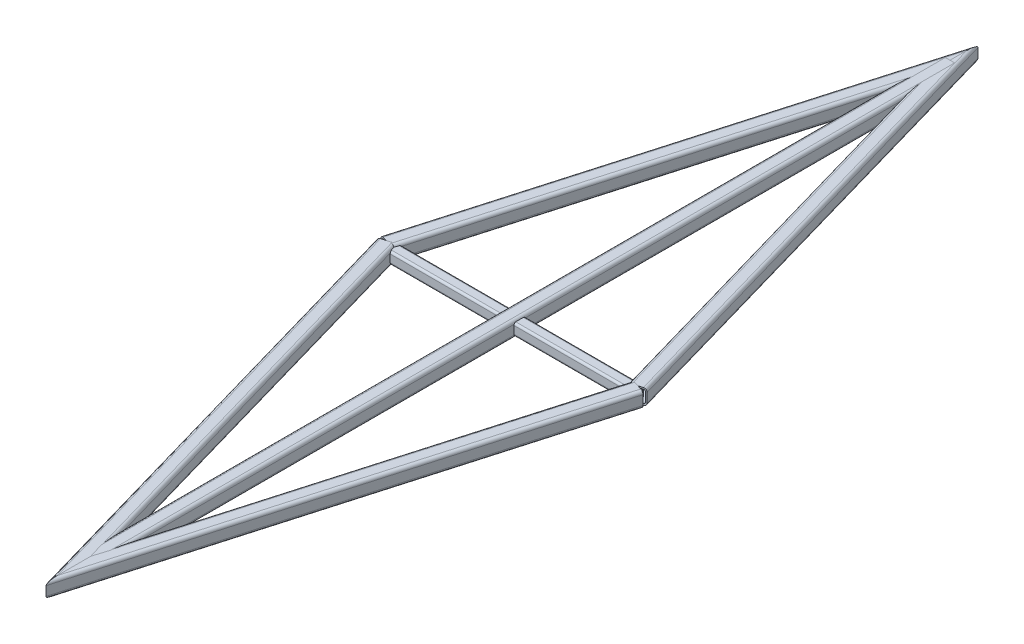
SolidWorks part; units mm, degrees
ref_plane "Front Plane" through (0, 0, 0) normal (0, 0, 1) x (1, 0, 0)
ref_plane "Top Plane" through (0, 0, 0) normal (0, 1, 0) x (1, 0, 0)
ref_plane "Right Plane" through (0, 0, 0) normal (1, 0, 0) x (0, 0, -1)
sketch "Sketch1" plane through (0, 0, 0) normal (0, 1, 0) x (1, 0, 0)
  circle A0 centre (0, 0) radius 465
  dimension "D1" = 930
sketch3d "3DSketch2"
  line L0 (325, 0, 332.5658) -> (325, 0, 1132.5658) construction
  line L1 (325, 0, 1132.5658) -> (-325, 0, 1132.5658) construction
  line L2 (-325, 0, 1132.5658) -> (-325, 0, 332.5658) construction
  line L3 (0, 0, 1132.5658) -> (0, 0, -1132.5658) construction
  line L4 (-465, 0, 0) -> (465, 0, 0) construction
  line L5 (325, 0, -332.5658) -> (325, 0, -1132.5658) construction
  line L6 (325, 0, -1132.5658) -> (-325, 0, -1132.5658) construction
  line L7 (-325, 0, -1132.5658) -> (-325, 0, -332.5658) construction
  line L8 (0, 0, 1132.5658) -> (0, 500, 1132.5658) construction
  line L11 (325, 0, 332.5658) -> (325, 500, 332.5658) construction
  line L12 (-325, 0, 332.5658) -> (-325, 500, 332.5658) construction
  line L13 (325, 500, 332.5658) -> (325, 500, -332.5658) construction
  line L16 (325, 0, -332.5658) -> (325, 500, -332.5658) construction
  line L17 (0, 500, 1132.5658) -> (325, 500, 0)
  line L19 (0, 500, 1132.5658) -> (-325, 500, 0)
  line L23 (0, 500, -1132.5658) -> (325, 500, 0)
  line L26 (0, 500, -1132.5658) -> (-325, 500, 0)
  line L28 (0, 500, 1132.5658) -> (0, 500, -1132.5658)
  line L29 (-325, 500, 0) -> (325, 500, 0) construction
  line L30 (325, 500, 0) -> (0, 500, 0) construction
  line L31 (0, 500, 0) -> (-325, 500, 0) construction
  line L42 (0, 500, 0) -> (325, 500, 0)
  line L43 (0, 500, 0) -> (-325, 500, 0)
  circle A0 centre (0, 0, 0) radius 465 construction
  point P4 (0, 465, 0)
  point P7 (0, 0, 1132.5658)
  point P14 (0, 0, 0)
  point P28 (0, 500, 500)
  dimension "D1" = 325
  dimension "D2" = 800
  dimension "D3" = 500
  dimension "D4" = 500
  dimension "D5" = 500
other "Square tube 40 X 40 X 4(2)"
ref_plane "Plane5" through (0, 500, -1132.5658) normal (0.2758, 0, 0.9612) x (0.9612, 0, -0.2758)
sketch "Sketch117" plane through (0, 500, -1132.5658) normal (0.2758, 0, 0.9612) x (0.9612, 0, -0.2758)
  line L0 (-12, -16) -> (12, -16)
  line L1 (-16, -12) -> (-16, 12)
  line L2 (12, 16) -> (-12, 16)
  line L3 (16, 12) -> (16, -12)
  line L4 (-12, -20) -> (12, -20)
  line L5 (-20, -12) -> (-20, 12)
  line L6 (12, 20) -> (-12, 20)
  line L7 (20, 12) -> (20, -12)
  arc A0 (20, 12) -> (12, 20) centre (12, 12) ccw
  arc A1 (12, -20) -> (20, -12) centre (12, -12) ccw
  arc A2 (-20, -12) -> (-12, -20) centre (-12, -12) ccw
  arc A3 (-12, 20) -> (-20, 12) centre (-12, 12) ccw
  arc A4 (-12, 16) -> (-16, 12) centre (-12, 12) ccw
  arc A5 (16, 12) -> (12, 16) centre (12, 12) ccw
  arc A6 (12, -16) -> (16, -12) centre (12, -12) ccw
  arc A7 (-16, -12) -> (-12, -16) centre (-12, -12) ccw
  point P0 (-20, 0)
  point P1 (20, 0)
  point P2 (0, 20)
  point P3 (0, -20)
  point P4 (0, 0)
  point P5 (-20, -20)
  point P6 (20, -20)
  point P7 (20, 20)
  point P8 (-20, 20)
  point P33 (0, 0)
  dimension "D1" = 8
  dimension "Thickness" = 4
  dimension "V_leg" = 40
other "Square tube 40 X 40 X 4(3)"
ref_plane "Plane6" through (0, 500, 1132.5658) normal (0, 0, -1) x (1, 0, 0)
sketch "Sketch118" plane through (0, 500, 1132.5658) normal (0, 0, -1) x (1, 0, 0)
  line L0 (-12, -16) -> (12, -16)
  line L1 (-16, -12) -> (-16, 12)
  line L2 (12, 16) -> (-12, 16)
  line L3 (16, 12) -> (16, -12)
  line L4 (-12, -20) -> (12, -20)
  line L5 (-20, -12) -> (-20, 12)
  line L6 (12, 20) -> (-12, 20)
  line L7 (20, 12) -> (20, -12)
  arc A0 (20, 12) -> (12, 20) centre (12, 12) ccw
  arc A1 (12, -20) -> (20, -12) centre (12, -12) ccw
  arc A2 (-20, -12) -> (-12, -20) centre (-12, -12) ccw
  arc A3 (-12, 20) -> (-20, 12) centre (-12, 12) ccw
  arc A4 (-12, 16) -> (-16, 12) centre (-12, 12) ccw
  arc A5 (16, 12) -> (12, 16) centre (12, 12) ccw
  arc A6 (12, -16) -> (16, -12) centre (12, -12) ccw
  arc A7 (-16, -12) -> (-12, -16) centre (-12, -12) ccw
  point P0 (-20, 0)
  point P1 (20, 0)
  point P2 (0, 20)
  point P3 (0, -20)
  point P4 (0, 0)
  point P5 (-20, -20)
  point P6 (20, -20)
  point P7 (20, 20)
  point P8 (-20, 20)
  point P33 (0, 0)
  dimension "D1" = 8
  dimension "Thickness" = 4
  dimension "V_leg" = 40
other "Square tube 40 X 40 X 4(4)"
ref_plane "Plane7" through (0, 500, 1132.5658) normal (0.2758, 0, -0.9612) x (-0.9612, 0, -0.2758)
sketch "Sketch119" plane through (0, 500, 1132.5658) normal (0.2758, 0, -0.9612) x (-0.9612, 0, -0.2758)
  line L0 (-12, -16) -> (12, -16)
  line L1 (-16, -12) -> (-16, 12)
  line L2 (12, 16) -> (-12, 16)
  line L3 (16, 12) -> (16, -12)
  line L4 (-12, -20) -> (12, -20)
  line L5 (-20, -12) -> (-20, 12)
  line L6 (12, 20) -> (-12, 20)
  line L7 (20, 12) -> (20, -12)
  arc A0 (20, 12) -> (12, 20) centre (12, 12) ccw
  arc A1 (12, -20) -> (20, -12) centre (12, -12) ccw
  arc A2 (-20, -12) -> (-12, -20) centre (-12, -12) ccw
  arc A3 (-12, 20) -> (-20, 12) centre (-12, 12) ccw
  arc A4 (-12, 16) -> (-16, 12) centre (-12, 12) ccw
  arc A5 (16, 12) -> (12, 16) centre (12, 12) ccw
  arc A6 (12, -16) -> (16, -12) centre (12, -12) ccw
  arc A7 (-16, -12) -> (-12, -16) centre (-12, -12) ccw
  point P0 (-20, 0)
  point P1 (20, 0)
  point P2 (0, 20)
  point P3 (0, -20)
  point P4 (0, 0)
  point P5 (-20, -20)
  point P6 (20, -20)
  point P7 (20, 20)
  point P8 (-20, 20)
  point P33 (0, 0)
  dimension "D1" = 8
  dimension "Thickness" = 4
  dimension "V_leg" = 40
other "Square tube 30 X 30 X 2.6(8)"
ref_plane "Plane9" through (0, 500, 0) normal (1, 0, 0) x (0, 0, -1)
sketch "Sketch123" plane through (0, 500, 0) normal (1, 0, 0) x (0, 0, -1)
  line L0 (-9.8, -12.4) -> (9.8, -12.4)
  line L1 (-12.4, -9.8) -> (-12.4, 9.8)
  line L2 (9.8, 12.4) -> (-9.8, 12.4)
  line L3 (12.4, 9.8) -> (12.4, -9.8)
  line L4 (-9.8, -15) -> (9.8, -15)
  line L5 (-15, -9.8) -> (-15, 9.8)
  line L6 (9.8, 15) -> (-9.8, 15)
  line L7 (15, 9.8) -> (15, -9.8)
  arc A0 (15, 9.8) -> (9.8, 15) centre (9.8, 9.8) ccw
  arc A1 (9.8, -15) -> (15, -9.8) centre (9.8, -9.8) ccw
  arc A2 (-15, -9.8) -> (-9.8, -15) centre (-9.8, -9.8) ccw
  arc A3 (-9.8, 15) -> (-15, 9.8) centre (-9.8, 9.8) ccw
  arc A4 (-9.8, 12.4) -> (-12.4, 9.8) centre (-9.8, 9.8) ccw
  arc A5 (12.4, 9.8) -> (9.8, 12.4) centre (9.8, 9.8) ccw
  arc A6 (9.8, -12.4) -> (12.4, -9.8) centre (9.8, -9.8) ccw
  arc A7 (-12.4, -9.8) -> (-9.8, -12.4) centre (-9.8, -9.8) ccw
  point P0 (-15, 0)
  point P1 (15, 0)
  point P2 (0, 15)
  point P3 (0, -15)
  point P4 (0, 0)
  point P5 (-15, -15)
  point P6 (15, -15)
  point P7 (15, 15)
  point P8 (-15, 15)
  point P33 (0, 0)
  dimension "D1" = 5.2
  dimension "Thickness" = 2.6
  dimension "V_leg" = 30
sketch3d "3DSketch3"
  line L0 (-500, 500, 0) -> (500, 500, 0)
  line L1 (500, 500, 0) -> (325, 0, 332.5658)
  line L2 (325, 0, 332.5658) -> (465, 0, 0)
  line L3 (465, 0, 0) -> (325, 0, -332.5658)
  line L4 (325, 0, -332.5658) -> (500, 500, 0)
  line L5 (500, 500, 0) -> (465, 0, 0)
  line L6 (325, 0, 332.5658) -> (238.2132, 500, 302.4362)
  line L7 (0, 500, 1132.5658) -> (325, 500, 0) construction
  line L8 (238.2132, 500, 302.4362) -> (500, 500, 0)
  line L9 (500, 500, 0) -> (238.2132, 500, -302.4362)
  line L10 (0, 500, -1132.5658) -> (325, 500, 0) construction
  line L11 (238.2132, 500, -302.4362) -> (325, 0, -332.5658)
  line L12 (-325, 0, 332.5658) -> (-465, 0, 0)
  line L13 (-238.2132, 500, -302.4362) -> (-325, 0, -332.5658)
  line L14 (-500, 500, 0) -> (-238.2132, 500, -302.4362)
  line L15 (-500, 500, 0) -> (-465, 0, 0)
  line L16 (-325, 0, -332.5658) -> (-500, 500, 0)
  line L17 (-465, 0, 0) -> (-325, 0, -332.5658)
  line L18 (-325, 0, 332.5658) -> (-238.2132, 500, 302.4362)
  line L19 (-500, 500, 0) -> (-325, 0, 332.5658)
  line L20 (-238.2132, 500, 302.4362) -> (-500, 500, 0)
  point P4 (0, 500, 0)
  dimension "D1" = 500
  dimension "D2" = 400
  dimension "D3" = 400
sketch "Sketch143" plane through (0, 0, 0) normal (0, 1, 0) x (1, 0, 0)
  line L1 (-813.6075, 1191.1064) -> (813.6075, 1191.1064)
  line L2 (-813.6075, 1191.1064) -> (-813.6075, -1191.1064)
  line L3 (-813.6075, -1191.1064) -> (813.6075, -1191.1064)
  line L4 (813.6075, 1191.1064) -> (813.6075, -1191.1064)
  line L5 (-813.6075, 1191.1064) -> (813.6075, -1191.1064) construction
  line L6 (-813.6075, -1191.1064) -> (813.6075, 1191.1064) construction
  point P0 (0, 0)
sketch "Sketch144" plane through (0, 480, 0) normal (0, -1, 0) x (1, 0, 0)
  line L0 (0, 320) -> (0, -320) construction
  circle A0 centre (0, 0) radius 320 construction
  dimension "D1" = 640
